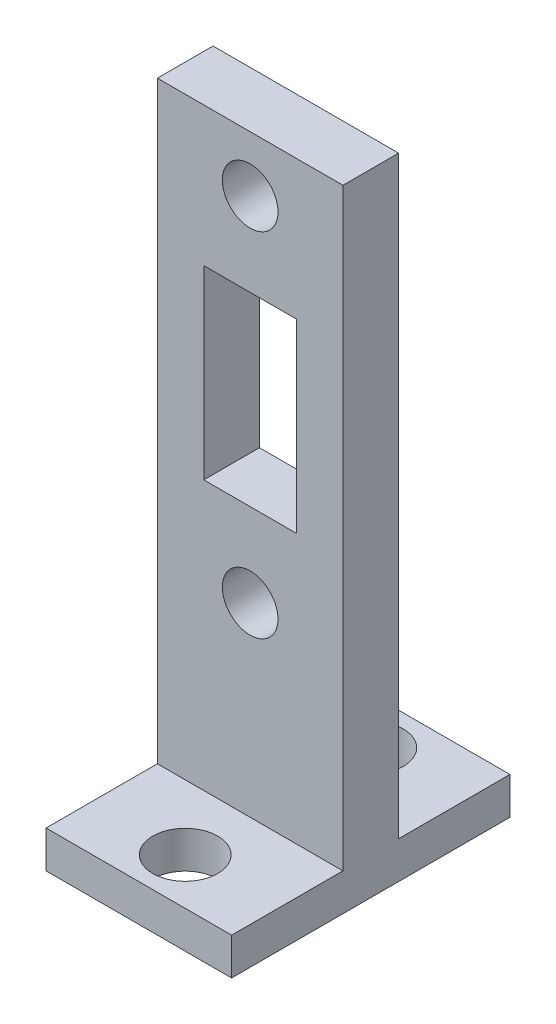
SolidWorks part; units mm, degrees
ref_plane "Alzado" through (0, 0, 0) normal (0, 0, 1) x (1, 0, 0)
ref_plane "Planta" through (0, 0, 0) normal (0, 1, 0) x (1, 0, 0)
ref_plane "Vista lateral" through (0, 0, 0) normal (1, 0, 0) x (0, 0, -1)
sketch "Croquis1" plane through (0, 0, 0) normal (0, 1, 0) x (1, 0, 0)
  line L1 (5, -7.5) -> (-5, -7.5)
  line L2 (5, -7.5) -> (5, 7.5)
  line L3 (5, 7.5) -> (-5, 7.5)
  line L4 (-5, -7.5) -> (-5, 7.5)
  line L5 (5, -7.5) -> (-5, 7.5) construction
  line L6 (5, 7.5) -> (-5, -7.5) construction
  circle A0 centre (0, 5) radius 1.75
  circle A1 centre (0, -5) radius 1.75
  point P0 (0, 0)
  dimension "D3" = 10
  dimension "D4" = 2.5
  dimension "D5" = 3.5
  dimension "3" = 3.5
  dimension "D1" = 15
  dimension "D2" = 10
extrude "Saliente-Extruir1" add sketch "Croquis1" along normal blind 2
sketch "Croquis2" plane through (0, 2, 0) normal (0, 1, 0) x (1, 0, 0)
  line L0 (5, -7.5) -> (5, 7.5) construction
  line L1 (-5, 1.5) -> (5, 1.5)
  line L2 (-5, 1.5) -> (-5, -1.5)
  line L3 (-5, -1.5) -> (5, -1.5)
  line L4 (5, 1.5) -> (5, -1.5)
  line L5 (-5, 1.5) -> (5, -1.5) construction
  line L6 (-5, -1.5) -> (5, 1.5) construction
  point P0 (0, 0)
  dimension "D1" = 3
extrude "Saliente-Extruir2" add sketch "Croquis2" along normal blind 32
sketch "Croquis3" plane through (0, 0, 1.5) normal (0, 0, 1) x (1, 0, 0)
  line L0 (0, 34) -> (0, 12) construction
  line L1 (-5, 34) -> (5, 34) construction
  circle A0 centre (0, 31) radius 1.5
  circle A1 centre (0, 12) radius 1.5
  dimension "D1" = 3
  dimension "D2" = 3
  dimension "D3" = 19
  dimension "D4" = 22
extrude "Cortar-Extruir1" cut sketch "Croquis3" against normal through all
sketch "Croquis4" plane through (0, 0, 1.5) normal (0, 0, 1) x (1, 0, 0)
  line L0 (0, 31) -> (0, 12) construction
  line L2 (-2.5, 26.5) -> (2.5, 26.5)
  line L3 (-2.5, 26.5) -> (-2.5, 16.5)
  line L4 (-2.5, 16.5) -> (2.5, 16.5)
  line L5 (2.5, 26.5) -> (2.5, 16.5)
  line L6 (-2.5, 26.5) -> (2.5, 16.5) construction
  line L7 (-2.5, 16.5) -> (2.5, 26.5) construction
  point P4 (0, 21.5)
  dimension "D1" = 5
  dimension "D2" = 10
extrude "Cortar-Extruir2" cut sketch "Croquis4" against normal through all
